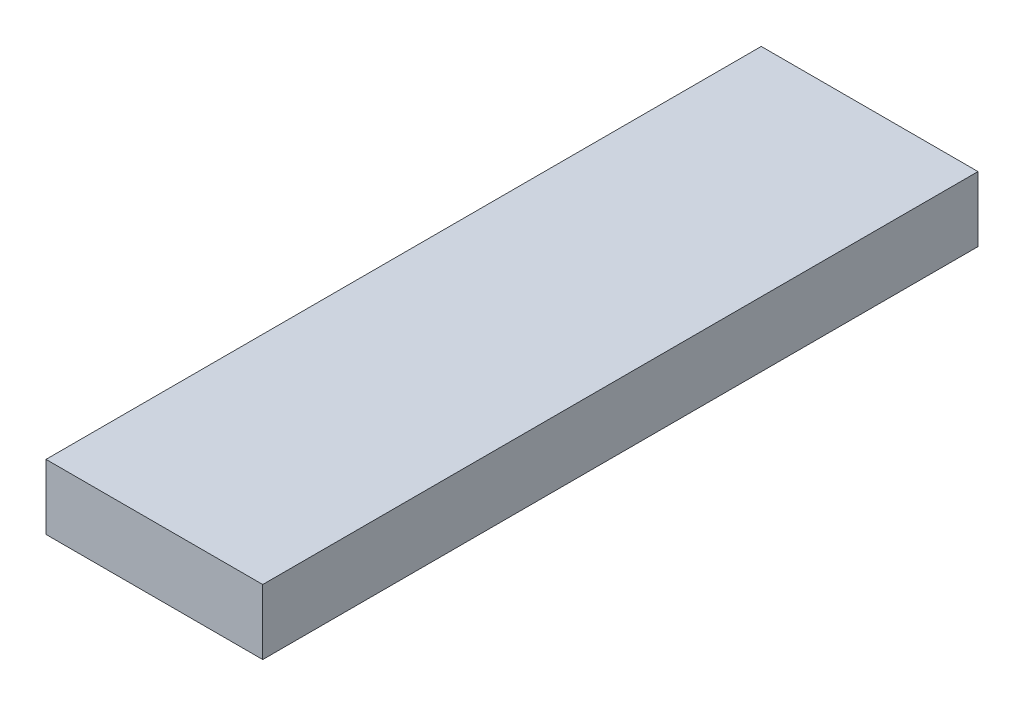
SolidWorks part; units mm, degrees
ref_plane "Front" through (0, 0, 0) normal (0, 0, 1) x (1, 0, 0)
ref_plane "Top" through (0, 0, 0) normal (0, 1, 0) x (1, 0, 0)
ref_plane "Right" through (0, 0, 0) normal (1, 0, 0) x (0, 0, -1)
sketch "草图1" plane through (0, 0, 0) normal (0, 1, 0) x (1, 0, 0)
  line L1 (-5, -16.5) -> (5, -16.5)
  line L2 (-5, -16.5) -> (-5, 16.5)
  line L3 (-5, 16.5) -> (5, 16.5)
  line L4 (5, -16.5) -> (5, 16.5)
  line L5 (-5, -16.5) -> (5, 16.5) construction
  line L6 (-5, 16.5) -> (5, -16.5) construction
  point P0 (0, 0)
  dimension "D1" = 10
  dimension "D2" = 33
extrude "凸台-拉伸1" add sketch "草图1" along normal blind 3
